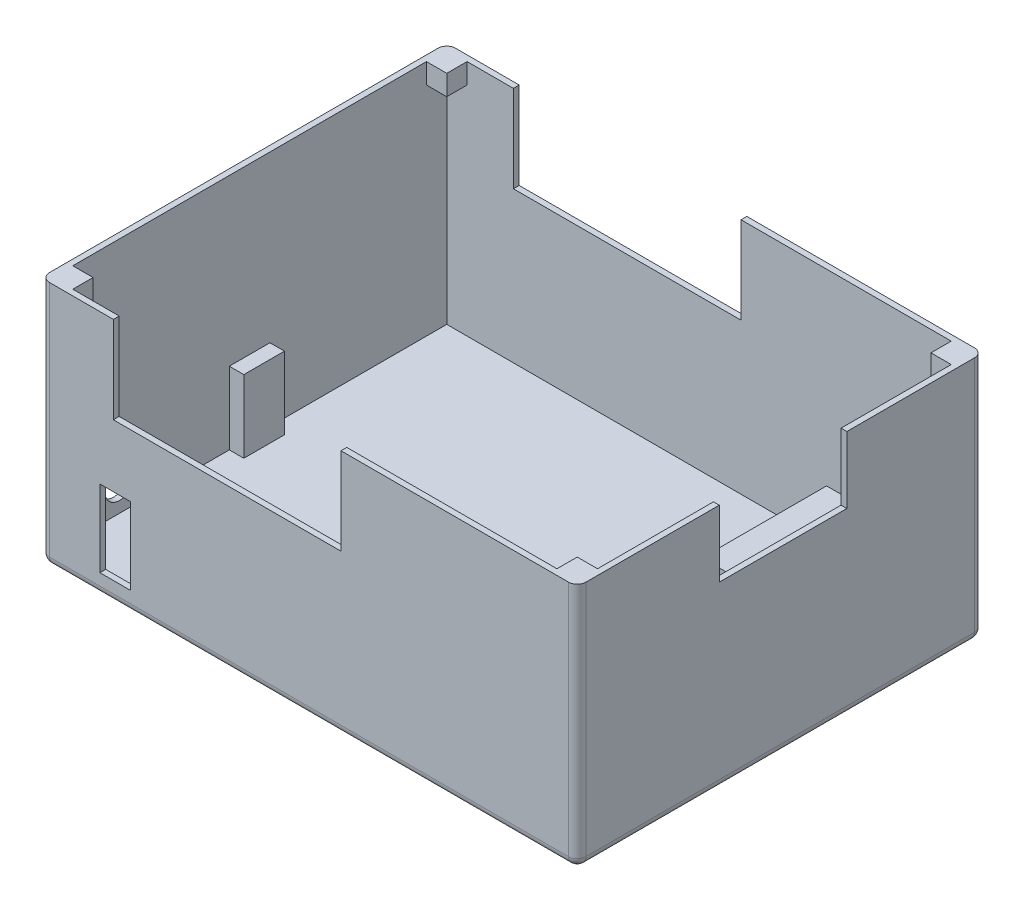
SolidWorks part; units mm, degrees
other "Markup1"
sketch "Sketch10" plane through (82.5, 85, 60) normal (0.5117, 0.7824, 0.3549) x (0.0047, 0.4105, -0.9118)
ref_plane "Front Plane" through (0, 0, 0) normal (0, 0, 1) x (1, 0, 0)
ref_plane "Top Plane" through (0, 0, 0) normal (0, 1, 0) x (1, 0, 0)
ref_plane "Right Plane" through (0, 0, 0) normal (1, 0, 0) x (0, 0, -1)
sketch "Sketch1" plane through (0, 0, 0) normal (0, 1, 0) x (1, 0, 0)
  line L1 (92.5, -70) -> (-92.5, -70)
  line L2 (92.5, -70) -> (92.5, 70)
  line L3 (92.5, 70) -> (-92.5, 70)
  line L4 (-92.5, -70) -> (-92.5, 70)
  line L5 (92.5, -70) -> (-92.5, 70) construction
  line L6 (92.5, 70) -> (-92.5, -70) construction
  point P0 (0, 0)
  dimension "D1" = 140
  dimension "D2" = 185
extrude "Boss-Extrude1" add sketch "Sketch1" along normal blind 85
sketch "Sketch2" plane through (0, 85, 0) normal (0, 1, 0) x (1, 0, 0)
  line L0 (-92.5, 70) -> (-92.5, -70) construction
  line L1 (90.5, -68) -> (-90.5, -68)
  line L2 (90.5, -68) -> (90.5, 68)
  line L3 (90.5, 68) -> (-90.5, 68)
  line L4 (-90.5, -68) -> (-90.5, 68)
  line L5 (90.5, -68) -> (-90.5, 68) construction
  line L6 (90.5, 68) -> (-90.5, -68) construction
  line L7 (92.5, -70) -> (92.5, 70) construction
  line L8 (92.5, 70) -> (-92.5, 70) construction
  line L9 (-92.5, -70) -> (92.5, -70) construction
  point P0 (0, 0)
  dimension "D1" = 2
  dimension "D2" = 2
  dimension "D3" = 2
  dimension "D4" = 2
extrude "Cut-Extrude1" cut sketch "Sketch2" against normal offset from surface (82 mm away) 3 up to face at (0, 0, 0)
sketch "Sketch3" plane through (0, 0, 70) normal (0, 0, 1) x (1, 0, 0)
  line L0 (-92.5, 85) -> (92.5, 85) construction
  line L1 (-67.5, 85) -> (-7.5, 85)
  line L2 (-67.5, 85) -> (-67.5, 55)
  line L3 (-67.5, 55) -> (-7.5, 55)
  line L4 (-7.5, 85) -> (-7.5, 55)
  line L5 (-92.5, 85) -> (-92.5, 0) construction
  dimension "D1" = 25
  dimension "D2" = 60
  dimension "D3" = 30
extrude "Cut-Extrude3" cut sketch "Sketch3" against normal up to surface (140 mm away) up to face at (0, 42.5, -70)
sketch "Sketch6" plane through (0, 0, 68) normal (0, 0, -1) x (-1, 0, 0)
  line L1 (90.5, 85) -> (83.5, 85)
  line L2 (90.5, 85) -> (90.5, 78)
  line L3 (90.5, 78) -> (83.5, 78)
  line L4 (83.5, 85) -> (83.5, 78)
  dimension "D1" = 7
  dimension "D2" = 7
extrude "Boss-Extrude2" add sketch "Sketch6" along normal blind 7
sketch "Sketch7" plane through (0, 0, -68) normal (0, 0, 1) x (1, 0, 0)
  line L1 (-90.5, 85) -> (-83.5, 85)
  line L2 (-90.5, 85) -> (-90.5, 78)
  line L3 (-90.5, 78) -> (-83.5, 78)
  line L4 (-83.5, 85) -> (-83.5, 78)
  dimension "D1" = 7
  dimension "D2" = 7
extrude "Boss-Extrude3" add sketch "Sketch7" along normal blind 7
sketch "Sketch8" plane through (0, 0, 68) normal (0, 0, -1) x (-1, 0, 0)
  line L1 (-90.5, 85) -> (-83.5, 85)
  line L2 (-90.5, 85) -> (-90.5, 78)
  line L3 (-90.5, 78) -> (-83.5, 78)
  line L4 (-83.5, 85) -> (-83.5, 78)
  dimension "D1" = 7
  dimension "D2" = 7
extrude "Boss-Extrude4" add sketch "Sketch8" along normal blind 7
sketch "Sketch9" plane through (0, 0, -68) normal (0, 0, 1) x (1, 0, 0)
  line L1 (90.5, 85) -> (83.5, 85)
  line L2 (90.5, 85) -> (90.5, 78)
  line L3 (90.5, 78) -> (83.5, 78)
  line L4 (83.5, 85) -> (83.5, 78)
  dimension "D1" = 7
  dimension "D2" = 7
extrude "Boss-Extrude5" add sketch "Sketch9" along normal blind 7
sketch "Sketch11" plane through (0, 3, 0) normal (0, 1, 0) x (1, 0, 0)
  line L0 (-90.5, 68) -> (90.5, 68) construction
  line L1 (40.5, 68) -> (90.5, 68)
  line L2 (40.5, 68) -> (40.5, 25)
  line L3 (40.5, 25) -> (90.5, 25)
  line L4 (90.5, 68) -> (90.5, 25)
  line L5 (90.5, 68) -> (90.5, -68) construction
  dimension "D1" = 43
  dimension "D2" = 50
  dimension "D3" = 0
extrude "Boss-Extrude6" add sketch "Sketch11" along normal blind 17.25
sketch "Sketch12" plane through (0, 3, 0) normal (0, 1, 0) x (1, 0, 0)
  line L1 (17.5, 7.5) -> (42.5, 7.5)
  line L2 (17.5, 7.5) -> (17.5, -7.5)
  line L3 (17.5, -7.5) -> (42.5, -7.5)
  line L4 (42.5, 7.5) -> (42.5, -7.5)
  dimension "D1" = 25
  dimension "D2" = 15
  dimension "D3" = 7.5
  dimension "D4" = 17.5
extrude "Boss-Extrude7" add sketch "Sketch12" along normal blind 6.5
sketch "Sketch13" plane through (0, 0, 70) normal (0, 0, 1) x (1, 0, 0)
  line L1 (-7.5, 85) -> (2.5, 85)
  line L2 (-7.5, 85) -> (-7.5, 55)
  line L3 (-7.5, 55) -> (2.5, 55)
  line L4 (2.5, 85) -> (2.5, 55)
  dimension "D1" = 10
extrude "Cut-Extrude4" cut sketch "Sketch13" against normal blind 174
sketch "Sketch14" plane through (-90.5, 0, 0) normal (1, 0, 0) x (0, 0, -1)
  line L0 (-68, 3) -> (68, 3) construction
  line L1 (-7, 3) -> (7, 3)
  line L2 (-7, 3) -> (-7, 28)
  line L3 (-7, 28) -> (7, 28)
  line L4 (7, 3) -> (7, 28)
  line L5 (68, 3) -> (68, 78) construction
  dimension "D1" = 14
  dimension "D2" = 25
  dimension "D3" = 61
extrude "Boss-Extrude8" add sketch "Sketch14" along normal blind 5
sketch "Sketch21" plane through (92.5, 0, 0) normal (1, 0, 0) x (0, 0, -1)
  line L0 (-70, 85) -> (70, 85) construction
  line L1 (23, 62) -> (-21, 62)
  line L2 (23, 62) -> (23, 85)
  line L3 (23, 85) -> (-21, 85)
  line L4 (-21, 62) -> (-21, 85)
  line L5 (23, 62) -> (-21, 85) construction
  line L6 (23, 85) -> (-21, 62) construction
  line L7 (-70, 85) -> (-70, 0) construction
  point P0 (1, 73.5)
  dimension "D1" = 23
  dimension "D2" = 44
  dimension "D3" = 49
extrude "Cut-Extrude11" cut sketch "Sketch21" against normal blind 12
sketch "Sketch23" plane through (-92.5, 0, 0) normal (-1, 0, 0) x (0, 0, 1)
  circle A0 centre (44.8956, 11.8415) radius 5
  dimension "D1" = 10
extrude "Cut-Extrude12" cut sketch "Sketch23" against normal blind 2
fillet "Fillet2" radius 3 8 edges at (-92.5, 0, 0) (-92.5, 42.5, -70) (0, 0, -70) (92.5, 42.5, -70) (92.5, 0, 0) (-92.5, 42.5, 70) (0, 0, 70) (92.5, 42.5, 70)
sketch "Sketch24" plane through (0, 0, -70) normal (0, 0, -1) x (-1, 0, 0)
  line L0 (-89.5, 85) -> (-2.5, 85) construction
  line L1 (-2.5, 55) -> (-9.5, 55)
  line L2 (-2.5, 55) -> (-2.5, 85)
  line L3 (-2.5, 85) -> (-9.5, 85)
  line L4 (-9.5, 55) -> (-9.5, 85)
  dimension "D1" = 7
extrude "Cut-Extrude13" cut sketch "Sketch24" against normal up to surface (140 mm away)
sketch "Sketch25" plane through (0, 0, -70) normal (0, 0, -1) x (-1, 0, 0)
  line L0 (-89.5, 85) -> (-9.5, 85) construction
  line L1 (-9.5, 55) -> (-11, 55)
  line L2 (-9.5, 55) -> (-9.5, 85)
  line L3 (-9.5, 85) -> (-11, 85)
  line L4 (-11, 55) -> (-11, 85)
  dimension "D1" = 1.5
extrude "Cut-Extrude14" cut sketch "Sketch25" against normal up to surface (140 mm away)
sketch "Sketch26" plane through (0, 3, 0) normal (0, 1, 0) x (1, 0, 0)
  line L0 (-67.5, -68) -> (11, -68) construction
  line L1 (11.0294, -19.944) -> (-6.6526, -19.944)
  line L2 (11.0294, -19.944) -> (11.0294, -35)
  line L3 (11.0294, -35) -> (-6.6526, -35)
  line L4 (-6.6526, -19.944) -> (-6.6526, -35)
  dimension "D1" = 17.682
  dimension "D2" = 33
extrude "Boss-Extrude12" add sketch "Sketch26" along normal blind 5
sketch "Sketch27" plane through (0, 0, 70) normal (0, 0, 1) x (1, 0, 0)
  line L0 (-89.5, 3) -> (89.5, 3) construction
  line L1 (-72.1287, 33.5) -> (-61.6287, 33.5)
  line L2 (-72.1287, 33.5) -> (-72.1287, 7)
  line L3 (-72.1287, 7) -> (-61.6287, 7)
  line L4 (-61.6287, 33.5) -> (-61.6287, 7)
  dimension "D1" = 10.5
  dimension "D2" = 4
  dimension "D3" = 26.5
extrude "Cut-Extrude15" cut sketch "Sketch27" against normal up to surface (2 mm away) up to face at (-9.4167, 64, 68)
